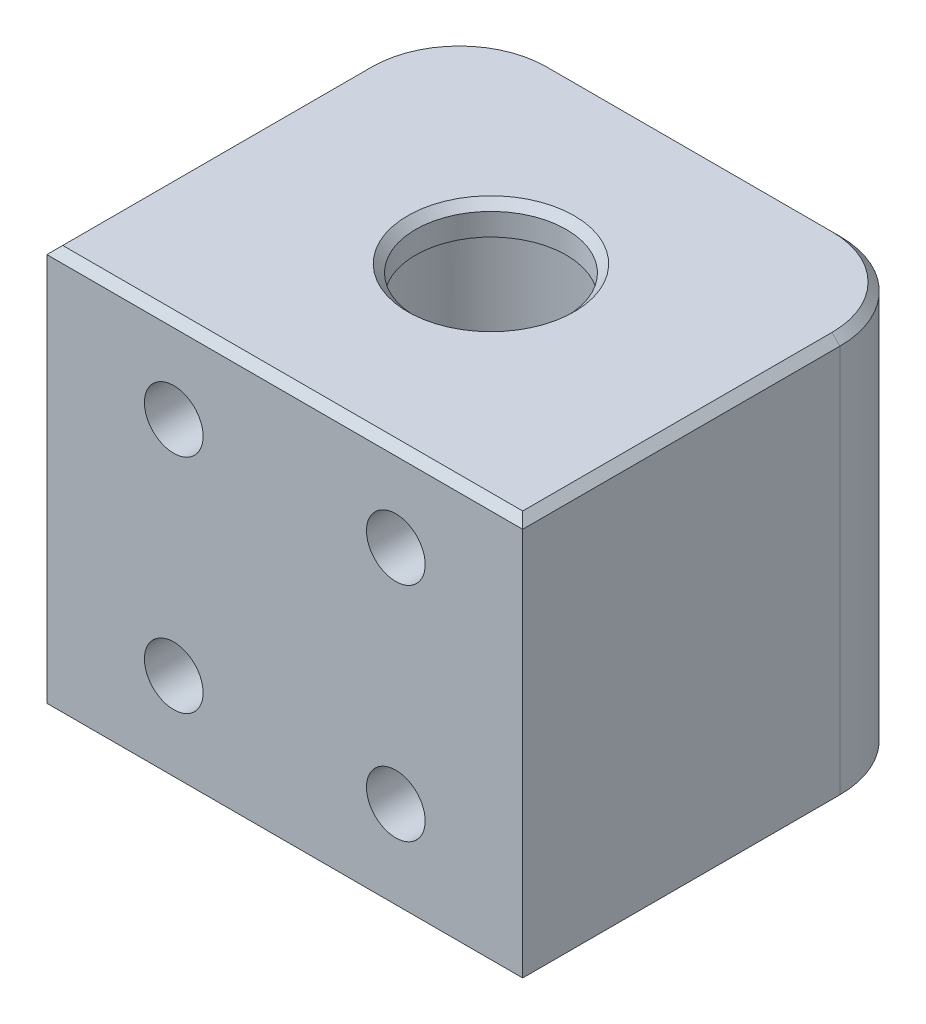
SolidWorks part; units mm, degrees
ref_plane "Front Plane" through (0, 0, 0) normal (0, 0, 1) x (1, 0, 0)
ref_plane "Top Plane" through (0, 0, 0) normal (0, 1, 0) x (1, 0, 0)
ref_plane "Right Plane" through (0, 0, 0) normal (1, 0, 0) x (0, 0, -1)
sketch "Sketch1" plane through (0, 0, 0) normal (0, 1, 0) x (1, 0, 0)
  line L1 (15, 13) -> (-15, 13)
  line L2 (15, 13) -> (15, -13)
  line L3 (15, -13) -> (-15, -13)
  line L4 (-15, 13) -> (-15, -13)
  line L5 (15, 13) -> (-15, -13) construction
  line L6 (15, -13) -> (-15, 13) construction
  point P0 (0, 0)
  dimension "D1" = 26
  dimension "D2" = 30
extrude "Boss-Extrude1" add sketch "Sketch1" along normal blind 25
sketch "Sketch7" [suppressed] plane through (0, 0, 0) normal (0, -1, 0) x (1, 0, 0)
  line L1 (10.3833, 6.5) -> (-10.3833, 6.5)
  line L3 (10.3833, -6.5) -> (-10.3833, -6.5)
  line L5 (10.3833, 6.5) -> (-10.3833, -6.5) construction
  line L6 (10.3833, -6.5) -> (-10.3833, 6.5) construction
  arc A0 (-10.3833, 6.5) -> (-10.3833, -6.5) centre (0, 0) ccw
  arc A1 (10.3833, 6.5) -> (10.3833, -6.5) centre (0, 0) cw
  point P0 (0, 0)
  dimension "D2" = 24.5
  dimension "D1" = 13
extrude "Cut-Extrude1" [suppressed] cut sketch "Sketch7" against normal blind 3.5
sketch "Sketch8" [suppressed] plane through (0, 3.5, 0) normal (0, -1, 0) x (1, 0, 0)
  circle A0 centre (0, 0) radius 5.25
  dimension "D1" = 10.5
extrude "Cut-Extrude2" [suppressed] cut sketch "Sketch8" against normal through all
sketch "Sketch9" [suppressed] plane through (0, 3.5, 0) normal (0, -1, 0) x (1, 0, 0)
  line L0 (9, 0) -> (-9, 0) construction
  point P1 (-9, 0)
  point P2 (9, 0)
  point P5 (0, 0)
  dimension "D1" = 18
hole_wizard "Ø2.7 (2.7) Diameter Hole2" [suppressed] positions "Sketch9" profile "Sketch11" hole size "Ø2.7" standard "ANSI Metric"
sketch "Sketch11" [suppressed] plane through (-9, 3.5, 0) normal (1, 0, 0) x (0, 0, -1)
  line L0 (0, 0) -> (0, 16.8112)
  line L1 (0, 16.8112) -> (1.35, 16)
  line L2 (1.35, 16) -> (1.35, 0)
  line L5 (1.35, 0) -> (0, 0)
  line L10 (0, 16.8112) -> (-1.35, 16) construction
  line L11 (0, -6.35) -> (0, 107.95) construction
  dimension "Hole Dia." = 2.7
  dimension "Hole Depth" = 16
  dimension "Drill Angle" = 118
sketch "Sketch2" [suppressed] plane through (0, 0, 0) normal (1, 0, 0) x (0, 0, -1)
  line L0 (0, 0) -> (11.25, 0)
  line L1 (13, 0) -> (-13, 0) construction
  line L2 (11.25, 0) -> (11.25, 3.5)
  line L3 (11.25, 3.5) -> (6.45, 3.5)
  line L4 (6.45, 3.5) -> (6.45, 21.5)
  line L5 (6.45, 21.5) -> (4.75, 21.5)
  line L6 (4.75, 21.5) -> (4.75, 25)
  line L7 (13, 25) -> (-13, 25) construction
  line L8 (4.75, 25) -> (0, 25)
  line L9 (0, 25) -> (0, 0) construction
  line L10 (0, 0) -> (0, 25)
  line L11 (-13, 25) -> (13, 25) construction
  dimension "D1" = 22.5
  dimension "D2" = 12.9
  dimension "D3" = 9.5
  dimension "D4" = 3.5
  dimension "D5" = 18
revolve "Cut-Revolve1" [suppressed] cut sketch "Sketch2" angle 360 about L9
sketch "Sketch3" [suppressed] plane through (0, 3.5, 0) normal (0, -1, 0) x (1, 0, 0)
  line L1 (6, 6) -> (-6, 6) construction
  line L2 (6, 6) -> (6, -6) construction
  line L3 (6, -6) -> (-6, -6) construction
  line L4 (-6, 6) -> (-6, -6) construction
  line L5 (6, 6) -> (-6, -6) construction
  line L6 (6, -6) -> (-6, 6) construction
  point P0 (0, 0)
  point P1 (-6, -6)
  point P2 (6, 6)
  point P3 (6, -6)
  point P4 (-6, 6)
  dimension "D1" = 12
hole_wizard "Ø2.7 (2.7) Diameter Hole1" [suppressed] positions "Sketch3" profile "Sketch4" hole size "Ø2.7" standard "ANSI Metric"
sketch "Sketch4" [suppressed] plane through (-6, 3.5, 6) normal (1, 0, 0) x (0, 0, -1)
  line L0 (0, 0) -> (0, 10.8112)
  line L1 (0, 10.8112) -> (1.35, 10)
  line L2 (1.35, 10) -> (1.35, 0)
  line L5 (1.35, 0) -> (0, 0)
  line L10 (0, 10.8112) -> (-1.35, 10) construction
  line L11 (0, -6.35) -> (0, 107.95) construction
  dimension "Hole Dia." = 2.7
  dimension "Hole Depth" = 10
  dimension "Drill Angle" = 118
sketch "Sketch12" plane through (0, 0, 0) normal (0, -1, 0) x (1, 0, 0)
  line L1 (13.0599, 6.3) -> (-13.0599, 6.3)
  line L3 (13.0599, -6.3) -> (-13.0599, -6.3)
  line L5 (13.0599, 6.3) -> (-13.0599, -6.3) construction
  line L6 (13.0599, -6.3) -> (-13.0599, 6.3) construction
  arc A0 (-13.0599, 6.3) -> (-13.0599, -6.3) centre (0, 0) ccw
  arc A1 (13.0599, -6.3) -> (13.0599, 6.3) centre (0, 0) ccw
  dimension "D1" = 29
  dimension "D2" = 12.6
extrude "Cut-Extrude3" cut sketch "Sketch12" against normal blind 3.5
sketch "Sketch5" plane through (0, 0, 13) normal (0, 0, 1) x (1, 0, 0)
  line L1 (-7, 5.5) -> (7, 5.5)
  line L2 (-7, 5.5) -> (-7, 19.5)
  line L3 (-7, 19.5) -> (7, 19.5)
  line L4 (7, 5.5) -> (7, 19.5)
  line L5 (-7, 5.5) -> (7, 19.5) construction
  line L6 (-7, 19.5) -> (7, 5.5) construction
  line L7 (15, 25) -> (15, 0) construction
  point P21 (0, 12.5)
  point P22 (7, 19.5)
  point P163 (-7, 5.5)
  point P164 (-7, 19.5)
  point P165 (7, 5.5)
  point P170 (15, 12.5)
  dimension "D1" = 14
hole_wizard "Ø3.7 (3.7) Diameter Hole1" positions "Sketch5" profile "Sketch6" hole size "Ø3.7" standard "ANSI Metric"
sketch "Sketch6" plane through (7, 5.5, 13) normal (1, 0, 0) x (0, -1, 0)
  line L0 (0, 0) -> (0, 5.1116)
  line L1 (0, 5.1116) -> (1.85, 4)
  line L2 (1.85, 4) -> (1.85, 0)
  line L5 (1.85, 0) -> (0, 0)
  line L10 (0, 5.1116) -> (-1.85, 4) construction
  line L11 (0, -6.35) -> (0, 107.95) construction
  dimension "Hole Dia." = 3.7
  dimension "Hole Depth" = 4
  dimension "Drill Angle" = 118
sketch "Sketch13" plane through (0, 0, 0) normal (0, 0, 1) x (1, 0, 0)
  line L0 (-6.6, 0) -> (-6.6, 23.1)
  line L2 (-6.6, 23.1) -> (-4.75, 23.1)
  line L3 (-4.75, 23.1) -> (-4.75, 25)
  line L4 (-15, 25) -> (15, 25) construction
  line L5 (-4.75, 25) -> (0, 25)
  line L6 (0, 0) -> (0, 25) construction
  line L7 (13.0599, 0) -> (-13.0599, 0) construction
  line L8 (-6.6, 0) -> (0, 0)
  line L9 (0, 0) -> (0, 25)
  line L10 (-13.0599, 3.5) -> (13.0599, 3.5) construction
  dimension "D1" = 9.5
  dimension "D2" = 13.2
  dimension "D3" = 19.6
revolve "Cut-Revolve2" cut sketch "Sketch13" angle 360 about L6
sketch "Sketch14" plane through (0, 3.5, 0) normal (0, -1, 0) x (1, 0, 0)
  line L0 (-9.25, 0) -> (9.25, 0) construction
  point P0 (-9.25, 0)
  point P1 (9.25, 0)
  point P3 (0, 0)
  dimension "D1" = 18.5
hole_wizard "Ø2.7 (2.7) Diameter Hole3" positions "Sketch14" profile "Sketch15" hole size "Ø2.7" standard "ANSI Metric"
sketch "Sketch15" plane through (-9.25, 3.5, 0) normal (1, 0, 0) x (0, 0, -1)
  line L0 (0, 0) -> (0, 12.8112)
  line L1 (0, 12.8112) -> (1.35, 12)
  line L2 (1.35, 12) -> (1.35, 0)
  line L5 (1.35, 0) -> (0, 0)
  line L10 (0, 12.8112) -> (-1.35, 12) construction
  line L11 (0, -6.35) -> (0, 107.95) construction
  dimension "Hole Dia." = 2.7
  dimension "Hole Depth" = 12
  dimension "Drill Angle" = 118
fillet "Fillet1" radius 6 2 edges at (15, 12.5, -13) (-15, 12.5, -13)
chamfer "Chamfer1" distance 0.5 angle 45 7 edges at (0, 25, 13) (-15, 25, 3) (-13.2426, 25, -11.2426) (0, 25, -13) (13.2426, 25, -11.2426) (15, 25, 3) (0, 25, -4.75)
